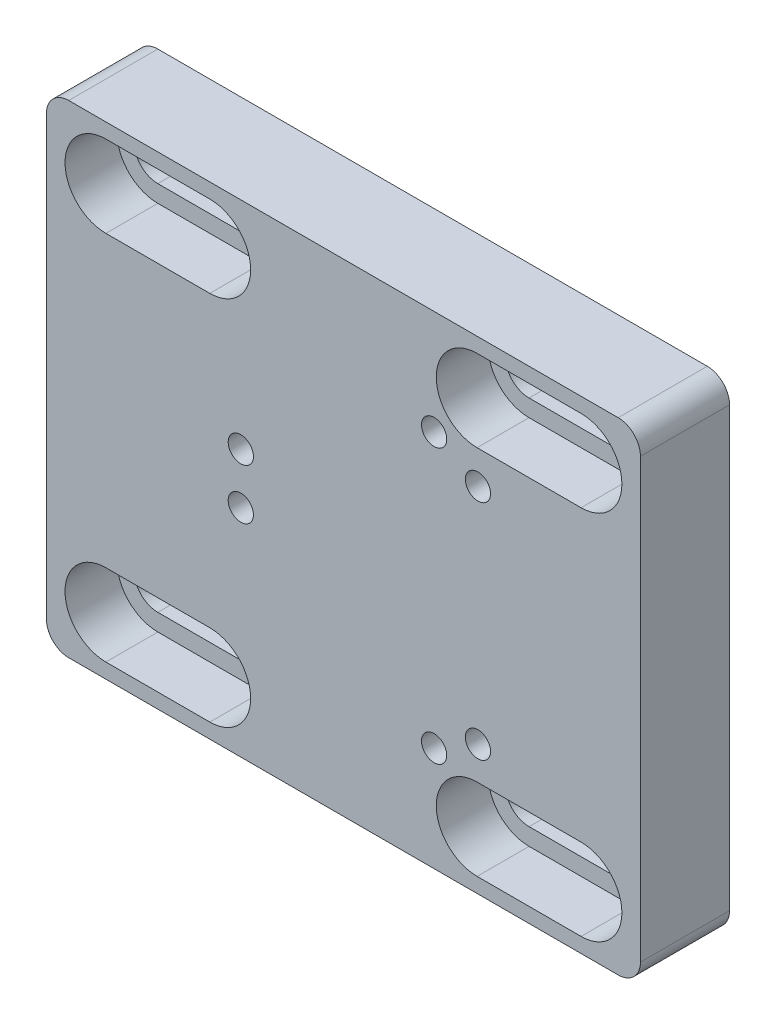
SolidWorks part; units mm, degrees
ref_plane "정면" through (0, 0, 0) normal (0, 0, 1) x (1, 0, 0)
ref_plane "윗면" through (0, 0, 0) normal (0, 1, 0) x (1, 0, 0)
ref_plane "우측면" through (0, 0, 0) normal (1, 0, 0) x (0, 0, -1)
sketch "스케치1" plane through (0, 0, 0) normal (0, 0, 1) x (1, 0, 0)
  line L0 (75, 39.2909) -> (75, -39.2909) construction
  line L1 (25, -25) -> (-25, -25) construction
  line L2 (25, -25) -> (25, 25) construction
  line L3 (25, 25) -> (-25, 25) construction
  line L4 (-25, -25) -> (-25, 25) construction
  line L5 (25, -25) -> (-25, 25) construction
  line L6 (25, 25) -> (-25, -25) construction
  line L7 (5.5, 39.2909) -> (5.5, -39.2909) construction
  line L8 (-21.2, 0) -> (32.2, 0) construction
  line L9 (-13.8239, 3.4073) -> (5.5, 0) construction
  line L12 (25, -25) -> (25, 25) construction
  line L13 (-40, -32.5) -> (-40, 32.5)
  line L15 (-40, 32.5) -> (40, 32.5)
  line L16 (40, 32.5) -> (40, -32.5)
  line L17 (40, -32.5) -> (-40, -32.5)
  circle A0 centre (5.5, 0) radius 26.7 construction
  circle A1 centre (5.5, 0) radius 19.622 construction
  circle A2 centre (-13.8239, -3.4073) radius 1.7
  circle A3 centre (-13.8239, 3.4073) radius 1.7
  circle A4 centre (18.1128, 15.0313) radius 1.7
  circle A5 centre (12.2111, 18.4386) radius 1.7
  circle A6 centre (12.2111, -18.4386) radius 1.7
  circle A7 centre (18.1128, -15.0313) radius 1.7
  circle A8 centre (0, 25) radius 3.2 construction
  circle A9 centre (0, -25) radius 3.2 construction
  circle A10 centre (25, -25) radius 3.2
  circle A11 centre (25, 25) radius 3.2
  circle A12 centre (-25, 25) radius 3.2
  circle A13 centre (-25, -25) radius 3.2
  circle A14 centre (-25, 25) radius 5 construction
  circle A15 centre (0, 25) radius 5 construction
  circle A16 centre (25, 25) radius 5 construction
  circle A17 centre (25, -25) radius 5 construction
  circle A18 centre (-25, -25) radius 5 construction
  point P0 (0, 0)
  point P8 (5.5, 0)
  point P9 (75, 0)
  point P21 (0, 0)
  point P33 (7.5, 0)
  point P40 (25, 0)
  point P48 (-40, 0)
  point P49 (40, 0)
  point P56 (9, 0)
  point P57 (5.5, 0)
  dimension "D3" = 53.4
  dimension "D4" = 39.244
  dimension "D5" = 3.4
  dimension "D9" = 6.4
  dimension "D10" = 6.4
  dimension "D14" = 6.4
  dimension "D15" = 6.4
  dimension "D17" = 10
  dimension "D1" = 75
  dimension "D6" = 170
  dimension "D11" = 50
  dimension "D12" = 50
  dimension "D13" = 50
  dimension "D16" = 40
  dimension "D18" = 65
  dimension "D19" = 40
  dimension "D21" = 5.5
  dimension "D7" = 3
extrude "보스-돌출1" add sketch "스케치1" along normal blind 12
sketch "스케치2" plane through (0, 0, 0) normal (0, 0, -1) x (-1, 0, 0)
  circle A0 centre (-12.2111, 18.4386) radius 3
  circle A1 centre (-18.1128, 15.0313) radius 3
  circle A2 centre (-12.2111, -18.4386) radius 3
  circle A3 centre (-18.1128, -15.0313) radius 3
  circle A4 centre (13.8239, -3.4073) radius 3
  circle A5 centre (13.8239, 3.4073) radius 3
  dimension "D1" = 6
extrude "컷-돌출1" cut sketch "스케치2" against normal blind 9.4
fillet "필렛1" radius 3 4 edges at (40, -32.5, 6) (-40, -32.5, 6) (-40, 32.5, 6) (40, 32.5, 6)
sketch "스케치3" plane through (0, 0, 12) normal (0, 0, 1) x (1, 0, 0)
  line L0 (-32, 25) -> (-18, 25) construction
  line L1 (-32, 30.5) -> (-18, 30.5)
  line L2 (-32, 19.5) -> (-18, 19.5)
  line L3 (32, 25) -> (18, 25) construction
  line L4 (32, 19.5) -> (18, 19.5)
  line L5 (32, 30.5) -> (18, 30.5)
  line L6 (32, -25) -> (18, -25) construction
  line L7 (32, -30.5) -> (18, -30.5)
  line L8 (32, -19.5) -> (18, -19.5)
  line L9 (-32, -25) -> (-18, -25) construction
  line L10 (-32, -19.5) -> (-18, -19.5)
  line L11 (-32, -30.5) -> (-18, -30.5)
  arc A0 (-32, 30.5) -> (-32, 19.5) centre (-32, 25) ccw
  arc A1 (-18, 19.5) -> (-18, 30.5) centre (-18, 25) ccw
  arc A2 (32, 19.5) -> (32, 30.5) centre (32, 25) ccw
  arc A3 (18, 30.5) -> (18, 19.5) centre (18, 25) ccw
  arc A4 (32, -30.5) -> (32, -19.5) centre (32, -25) ccw
  arc A5 (18, -19.5) -> (18, -30.5) centre (18, -25) ccw
  arc A6 (-32, -19.5) -> (-32, -30.5) centre (-32, -25) ccw
  arc A7 (-18, -30.5) -> (-18, -19.5) centre (-18, -25) ccw
  point P3 (-25, 25)
  point P11 (25, 25)
  point P22 (25, -25)
  point P29 (-25, -25)
  dimension "D1" = 5.5
  dimension "D2" = 14
  dimension "D3" = 14
  dimension "D4" = 14
  dimension "D5" = 14
extrude "컷-돌출2" cut sketch "스케치3" against normal blind 7
sketch "스케치4" plane through (0, 0, 5) normal (0, 0, 1) x (1, 0, 0)
  line L0 (-32, 25) -> (-18, 25) construction
  line L1 (-32, 28.2) -> (-18, 28.2)
  line L2 (-32, 21.8) -> (-18, 21.8)
  line L3 (18, 25) -> (32, 25) construction
  line L4 (18, 28.2) -> (32, 28.2)
  line L5 (18, 21.8) -> (32, 21.8)
  line L6 (32, -25) -> (18, -25) construction
  line L7 (32, -28.2) -> (18, -28.2)
  line L8 (32, -21.8) -> (18, -21.8)
  line L9 (-32, -25) -> (-18, -25) construction
  line L10 (-32, -21.8) -> (-18, -21.8)
  line L11 (-32, -28.2) -> (-18, -28.2)
  arc A0 (-32, 28.2) -> (-32, 21.8) centre (-32, 25) ccw
  arc A1 (-18, 21.8) -> (-18, 28.2) centre (-18, 25) ccw
  arc A2 (18, 28.2) -> (18, 21.8) centre (18, 25) ccw
  arc A3 (32, 21.8) -> (32, 28.2) centre (32, 25) ccw
  arc A4 (32, -28.2) -> (32, -21.8) centre (32, -25) ccw
  arc A5 (18, -21.8) -> (18, -28.2) centre (18, -25) ccw
  arc A6 (-32, -21.8) -> (-32, -28.2) centre (-32, -25) ccw
  arc A7 (-18, -28.2) -> (-18, -21.8) centre (-18, -25) ccw
  point P2 (-25, 25)
  point P9 (25, 25)
  point P17 (25, -25)
  point P25 (-25, -25)
  dimension "D1" = 3.2
  dimension "D2" = 14
  dimension "D3" = 14
  dimension "D4" = 14
  dimension "D5" = 14
extrude "컷-돌출3" cut sketch "스케치4" against normal through all
